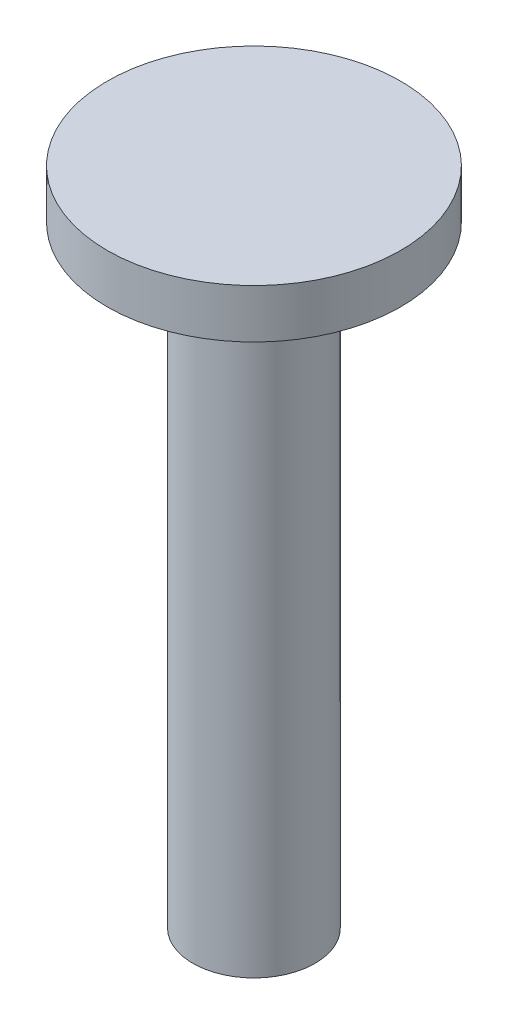
SolidWorks part; units mm, degrees
material "AISI 304"
ref_plane "前视基准面" through (0, 0, 0) normal (0, 0, 1) x (1, 0, 0)
ref_plane "上视基准面" through (0, 0, 0) normal (0, 1, 0) x (1, 0, 0)
ref_plane "右视基准面" through (0, 0, 0) normal (1, 0, 0) x (0, 0, -1)
other "Configuration Table"
sketch "草图1" plane through (0, 0, 0) normal (0, 1, 0) x (1, 0, 0)
  circle A0 centre (0, 0) radius 2.4
  dimension "D1" = 4.8
extrude "凸台-拉伸1" add sketch "草图1" along normal blind 0.8
sketch "草图2" plane through (0, 0, 0) normal (0, -1, 0) x (1, 0, 0)
  circle A0 centre (0, 0) radius 1
  dimension "D1" = 2
extrude "凸台-拉伸2" add sketch "草图2" along normal blind 10
